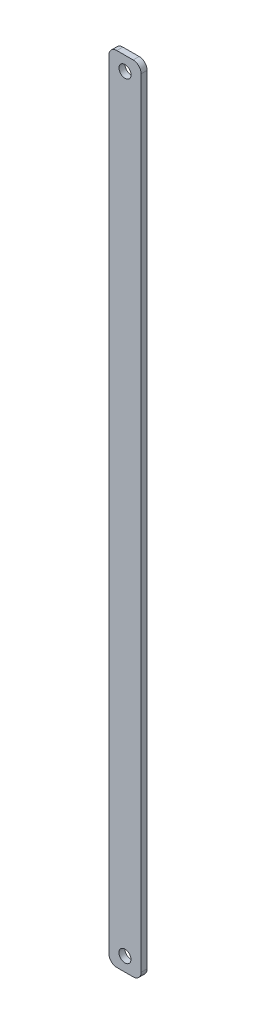
SolidWorks part; units mm, degrees
material "5052-H32"
ref_plane "Front Plane" through (0, 0, 0) normal (0, 0, 1) x (1, 0, 0)
ref_plane "Top Plane" through (0, 0, 0) normal (0, 1, 0) x (1, 0, 0)
ref_plane "Right Plane" through (0, 0, 0) normal (1, 0, 0) x (0, 0, -1)
sketch "Sketch1" plane through (0, 0, 0) normal (0, 1, 0) x (1, 0, 0)
  line L1 (-4.035, -0.75) -> (4.035, -0.75)
  line L2 (-4.035, -0.75) -> (-4.035, 0.75)
  line L3 (-4.035, 0.75) -> (4.035, 0.75)
  line L4 (4.035, -0.75) -> (4.035, 0.75)
  line L5 (-4.035, -0.75) -> (4.035, 0.75) construction
  line L6 (-4.035, 0.75) -> (4.035, -0.75) construction
  point P0 (0, 0)
  dimension "D1" = 8.07
  dimension "D2" = 1.5
extrude "Boss-Extrude1" add sketch "Sketch1" along normal blind 198.5
sketch "Sketch2" plane through (0, 0, 0.75) normal (0, 0, 1) x (1, 0, 0)
  line L0 (-4.035, 198.5) -> (-4.035, 0) construction
  line L1 (-4.035, 198.5) -> (4.035, 198.5) construction
  line L3 (4.035, 198.5) -> (4.035, 0) construction
  circle A0 centre (-0.005, 3.5) radius 1.5
  circle A1 centre (0.005, 195) radius 1.5
  dimension "D2" = 3
  dimension "D4" = 3
  dimension "D1" = 3.5
  dimension "D3" = 4.03
  dimension "D5" = 3.5
  dimension "D6" = 4.03
extrude "Cut-Extrude1" cut sketch "Sketch2" against normal up to surface (1.5 mm away) up to face at (0, 99.25, -0.75)
fillet "Fillet1" radius 2 4 edges at (-4.035, 0, 0) (4.035, 0, 0) (-4.035, 198.5, 0) (4.035, 198.5, 0)
